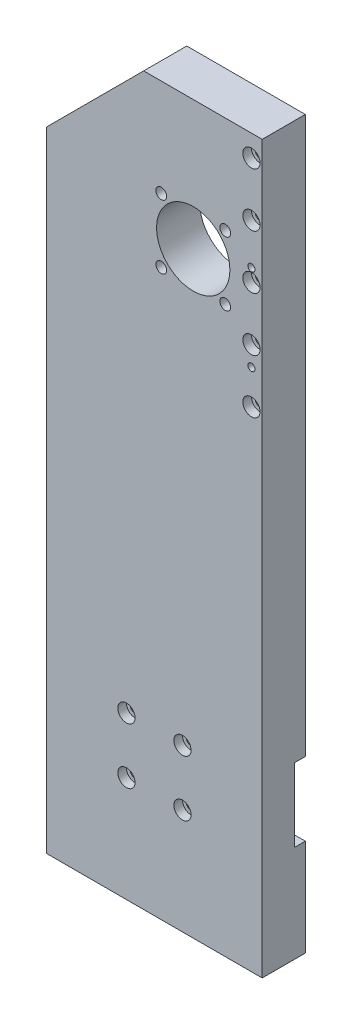
SolidWorks part; units mm, degrees
ref_plane "Front Plane" through (0, 0, 0) normal (0, 0, 1) x (1, 0, 0)
ref_plane "Top Plane" through (0, 0, 0) normal (0, 1, 0) x (1, 0, 0)
ref_plane "Right Plane" through (0, 0, 0) normal (1, 0, 0) x (0, 0, -1)
sketch "Sketch1" plane through (0, 0, 0) normal (0, 0, 1) x (1, 0, 0)
  line L0 (65.7045, 560.5004) -> (50.8553, 575.3496) construction
  line L1 (65.7045, 560.5004) -> (44.7045, 560.5004) construction
  line L2 (65.7045, 560.5004) -> (65.7045, 581.5004) construction
  line L3 (47.7045, 545.8558) -> (47.7045, 439.2537) construction
  line L4 (7.7288, 345.5004) -> (63.5732, 345.5004) construction
  line L5 (97.7045, 283.5004) -> (-2.2955, 283.5004)
  line L6 (97.7045, 283.5004) -> (97.7045, 620.5004)
  line L7 (97.7045, 620.5004) -> (-2.2955, 620.5004)
  line L8 (-2.2955, 283.5004) -> (-2.2955, 620.5004)
  line L9 (97.7045, 283.5004) -> (-2.2955, 620.5004) construction
  line L10 (97.7045, 620.5004) -> (-2.2955, 283.5004) construction
  circle A0 centre (65.7045, 560.5004) radius 17
  circle A1 centre (65.7045, 560.5004) radius 21 construction
  circle A2 centre (80.5538, 575.3496) radius 2.5
  circle A3 centre (80.5538, 545.6511) radius 2.5
  circle A4 centre (50.8553, 545.6511) radius 2.5
  circle A5 centre (50.8553, 575.3496) radius 2.5
  circle A6 centre (34.7045, 358.5004) radius 2
  circle A7 centre (60.7045, 358.5004) radius 2
  circle A8 centre (34.7045, 332.5004) radius 2
  circle A9 centre (60.7045, 332.5004) radius 2
  point P5 (50.8553, 575.3496)
  point P6 (80.5538, 575.3496)
  point P7 (80.5538, 545.6511)
  point P8 (50.8553, 545.6511)
  point P19 (47.7045, 452.0004)
  point P35 (34.7045, 358.5004)
  point P36 (60.7045, 358.5004)
  point P37 (60.7045, 332.5004)
  point P38 (34.7045, 332.5004)
  dimension "D2" = 5
  dimension "D3" = 34
  dimension "D4" = 42
  dimension "D10" = 4
  dimension "D1" = 45
  dimension "D5" = 337
  dimension "D6" = 100
  dimension "D7" = 60
  dimension "D8" = 75
  dimension "D9" = 13
  dimension "D11" = 62
  dimension "D12" = 32
extrude "Boss-Extrude1" add sketch "Sketch1" along normal blind 20
chamfer "Chamfer1" distance 45 angle 45 1 edges at (-2.2955, 620.5004, 10)
sketch "Sketch2" plane through (0, 0, 0) normal (0, 0, 1) x (1, 0, 0)
  line L0 (60.7045, 358.5004) -> (34.7045, 332.5004) construction
  line L1 (34.7045, 358.5004) -> (60.7045, 332.5004) construction
  line L3 (97.7045, 328.5004) -> (-2.2955, 328.5004)
  line L4 (97.7045, 328.5004) -> (97.7045, 362.5004)
  line L5 (97.7045, 362.5004) -> (-2.2955, 362.5004)
  line L6 (-2.2955, 328.5004) -> (-2.2955, 362.5004)
  line L7 (97.7045, 328.5004) -> (-2.2955, 362.5004) construction
  line L8 (97.7045, 362.5004) -> (-2.2955, 328.5004) construction
  point P8 (47.7045, 345.5004)
  point P9 (47.7045, 345.5004)
  dimension "D1" = 100
  dimension "D2" = 34
extrude "Cut-Extrude1" cut sketch "Sketch2" along normal blind 5
sketch "Sketch3" plane through (0, 0, 20) normal (0, 0, 1) x (1, 0, 0)
  line L0 (92.7045, 620.5004) -> (92.7045, 500.5004) construction
  line L1 (97.7045, 620.5004) -> (87.7045, 620.5004) construction
  line L2 (97.7045, 620.5004) -> (97.7045, 500.5004) construction
  line L3 (97.7045, 500.5004) -> (87.7045, 500.5004) construction
  line L4 (87.7045, 620.5004) -> (87.7045, 500.5004) construction
  line L5 (97.7045, 560.5004) -> (87.7045, 560.5004) construction
  point P9 (92.7045, 535.5004)
  point P10 (92.7045, 585.5004)
  point P11 (92.7045, 560.5004)
  point P12 (92.7045, 610.5004)
  point P13 (92.7045, 510.5004)
  dimension "D1" = 10
  dimension "D2" = 120
  dimension "D3" = 3
hole_wizard "CBORE for M4 SHCS1" positions "Sketch5" profile "Sketch6" counterbore size "M4" standard "ANSI Metric" end condition through all
sketch "Sketch5" plane through (0, 0, 20) normal (0, 0, 1) x (1, 0, 0)
  point P0 (92.7045, 610.5004)
  point P5 (92.7045, 585.5004)
  point P8 (92.7045, 560.5004)
  point P11 (92.7045, 535.5004)
  point P14 (92.7045, 510.5004)
sketch "Sketch6" plane through (92.7045, 610.5004, 20) normal (1, 0, 0) x (0, -1, 0)
  line L0 (0, 0) -> (0, 20)
  line L1 (0, 20) -> (2.25, 20)
  line L3 (2.25, 20) -> (2.25, 4)
  line L4 (2.25, 4) -> (4, 4)
  line L5 (4, 4) -> (4, 0)
  line L7 (4, 0) -> (0, 0)
  line L11 (0, -6.35) -> (0, 107.95) construction
  dimension "Thru Hole Dia." = 4.5
  dimension "Thru Hole Depth" = 20
  dimension "C'Bore Dia." = 8
  dimension "C'Bore Depth" = 4
hole_wizard "CBORE for M4 SHCS2" positions "3DSketch2" profile "Sketch10" counterbore size "M4" standard "ANSI Metric" end condition through all
sketch3d "3DSketch2"
  line L0 (34.7045, 358.5004, 20) -> (34.7045, 358.5004, 5) construction
  line L1 (60.7045, 358.5004, 20) -> (60.7045, 358.5004, 5) construction
  line L2 (34.7045, 332.5004, 20) -> (34.7045, 332.5004, 5) construction
  line L3 (60.7045, 332.5004, 20) -> (60.7045, 332.5004, 5) construction
  point P0 (34.7045, 358.5004, 20)
  point P4 (60.7045, 358.5004, 20)
  point P8 (34.7045, 332.5004, 20)
  point P12 (60.7045, 332.5004, 20)
sketch "Sketch10" plane through (34.7045, 358.5004, 20) normal (1, 0, 0) x (0, -1, 0)
  line L0 (0, 0) -> (0, 20)
  line L1 (0, 20) -> (2.25, 20)
  line L3 (2.25, 20) -> (2.25, 4)
  line L4 (2.25, 4) -> (4, 4)
  line L5 (4, 4) -> (4, 0)
  line L7 (4, 0) -> (0, 0)
  line L11 (0, -6.35) -> (0, 107.95) construction
  dimension "Thru Hole Dia." = 4.5
  dimension "Thru Hole Depth" = 20
  dimension "C'Bore Dia." = 8
  dimension "C'Bore Depth" = 4
sketch "Sketch11" plane through (0, 283.5004, 0) normal (0, -1, 0) x (1, 0, 0)
  line L0 (-2.2955, 10) -> (97.7045, 10) construction
  line L1 (-2.2955, 20) -> (-2.2955, 0) construction
  line L2 (97.7045, 20) -> (97.7045, 0) construction
  line L3 (47.7045, 20) -> (47.7045, 0) construction
  line L4 (-2.2955, 20) -> (97.7045, 20) construction
  line L5 (-2.2955, 0) -> (97.7045, 0) construction
  point P12 (67.7045, 10)
  point P13 (87.7045, 10)
  point P14 (47.7045, 10)
  point P15 (7.7045, 10)
  point P16 (27.7045, 10)
  dimension "D1" = 20
  dimension "D2" = 40
hole_wizard "M4 Tapped Hole1" positions "3DSketch3" profile "Sketch12" tap size "M4" standard "ISO"
sketch3d "3DSketch3"
  point P0 (7.7045, 283.5004, 10)
  point P3 (27.7045, 283.5004, 10)
  point P6 (67.7045, 283.5004, 10)
  point P9 (87.7045, 283.5004, 10)
sketch "Sketch12" plane through (7.7045, 283.5004, 10) normal (1, 0, 0) x (0, 0, -1)
  line L0 (0, 0) -> (0, 17.0914)
  line L1 (0, 17.0914) -> (1.65, 16.1)
  line L2 (1.65, 16.1) -> (1.65, 0)
  line L5 (1.65, 0) -> (0, 0)
  line L10 (0, 17.0914) -> (-1.65, 16.1) construction
  line L11 (0, -6.35) -> (0, 107.95) construction
  dimension "Tap Drill Dia." = 3.3
  dimension "Tap Drill Depth" = 16.1
  dimension "Drill Angle" = 118
sketch "Sketch13" plane through (0, 0, 20) normal (0, 0, 1) x (1, 0, 0)
  line L0 (90.1231, 566.406) -> (94.1231, 566.406) construction
  line L1 (90.1231, 567.906) -> (90.1231, 564.906) construction
  line L2 (94.1231, 564.906) -> (94.1231, 567.906) construction
  line L3 (92.7045, 571.5696) -> (92.7045, 564.5939) construction
  line L4 (92.7045, 531.5696) -> (92.7045, 524.5939) construction
  line L5 (94.1231, 526.406) -> (90.1231, 526.406) construction
  line L6 (94.1231, 524.906) -> (94.1231, 527.906) construction
  line L7 (90.1231, 527.906) -> (90.1231, 524.906) construction
  line L8 (92.7045, 620.5004) -> (92.7045, 500.5004) construction
  point P28 (92.7045, 566.406)
  point P29 (92.7045, 526.406)
  dimension "D1" = 40
hole_wizard "M4 Tapped Hole2" positions "Sketch16" profile "Sketch15" tap size "M4" standard "ISO" end condition through all
sketch "Sketch16" plane through (0, 0, 20) normal (0, 0, 1) x (1, 0, 0)
  point P0 (92.7045, 566.406)
  point P3 (92.7045, 526.406)
sketch "Sketch15" plane through (92.7045, 566.406, 20) normal (1, 0, 0) x (0, -1, 0)
  line L0 (0, 0) -> (0, 20)
  line L1 (0, 20) -> (1.65, 20)
  line L2 (1.65, 20) -> (1.65, 0)
  line L5 (1.65, 0) -> (0, 0)
  line L11 (0, -6.35) -> (0, 107.95) construction
  dimension "Thread Major Dia." = 3.3
  dimension "Thru Tap Drill Depth" = 20
